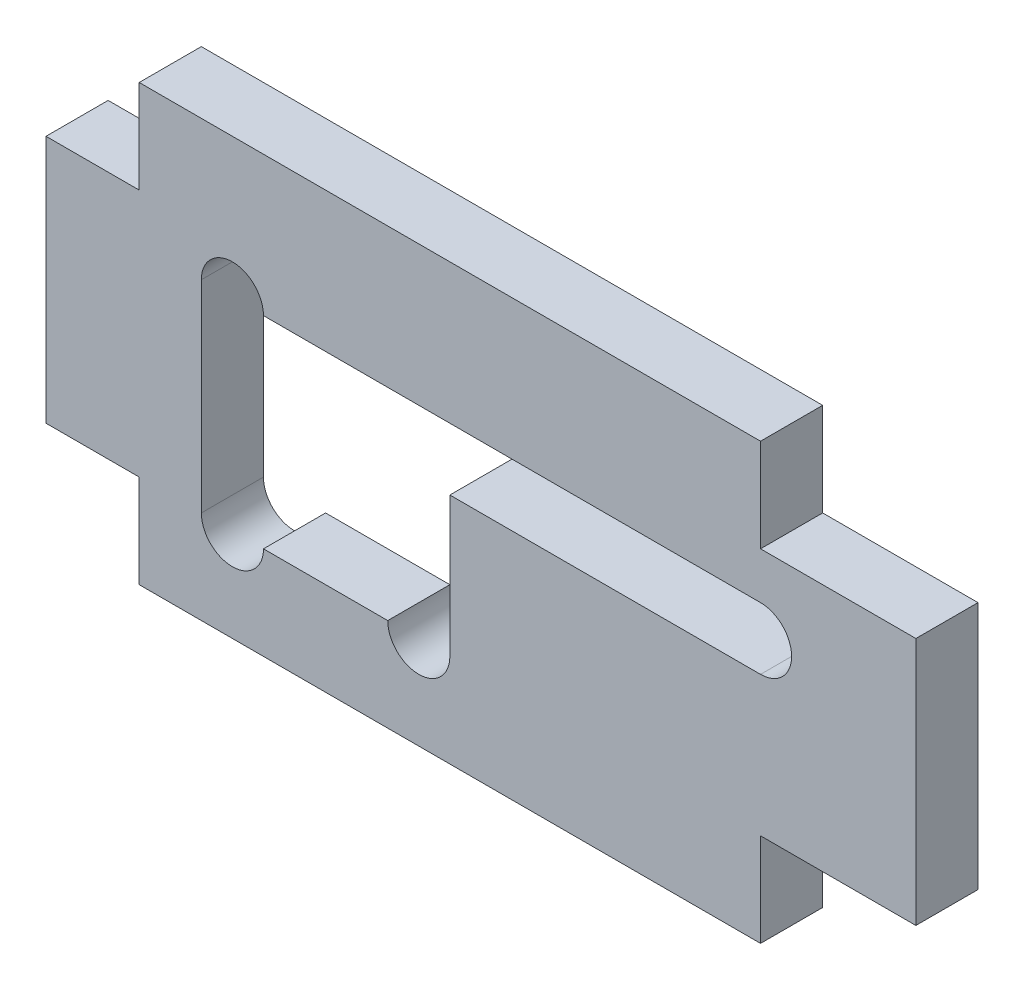
SolidWorks part; units mm, degrees
ref_plane "Front Plane" through (0, 0, 0) normal (0, 0, 1) x (1, 0, 0)
ref_plane "Top Plane" through (0, 0, 0) normal (0, 1, 0) x (1, 0, 0)
ref_plane "Right Plane" through (0, 0, 0) normal (1, 0, 0) x (0, 0, -1)
sketch "Sketch2" plane through (0, 0, 0) normal (0, 0, 1) x (1, 0, 0)
  line L0 (-100.4852, 17.2209) -> (-80.4852, 17.2209)
  line L1 (-80.4852, 17.2209) -> (-80.4852, 14.2209)
  line L2 (-80.4852, 14.2209) -> (-70.4852, 14.2209)
  line L3 (-70.4852, 14.2209) -> (-70.4852, 6.2209)
  line L4 (-70.4852, 6.2209) -> (-80.4852, 6.2209)
  line L5 (-80.4852, 6.2209) -> (-80.4852, 3.2209)
  line L6 (-80.4852, 3.2209) -> (-100.4852, 3.2209)
  line L7 (-100.4852, 3.2209) -> (-100.4852, 6.2209)
  line L8 (-100.4852, 6.2209) -> (-103.4852, 6.2209)
  line L9 (-103.4852, 6.2209) -> (-103.4852, 14.2209)
  line L10 (-103.4852, 14.2209) -> (-100.4852, 14.2209)
  line L11 (-100.4852, 14.2209) -> (-100.4852, 17.2209)
  line L13 (-90.4852, 10.7209) -> (-80.4852, 10.7209)
  line L14 (-98.4852, 12.7209) -> (-98.4852, 6.2209)
  line L16 (-90.4852, 6.2209) -> (-90.4852, 10.7209)
  line L17 (-96.4852, 12.7209) -> (-80.4852, 12.7209)
  line L18 (-96.4852, 6.2209) -> (-92.4852, 6.2209)
  arc A0 (-80.4852, 10.7209) -> (-80.4852, 12.7209) centre (-80.4852, 11.7209) ccw
  arc A1 (-96.4852, 12.7209) -> (-98.4852, 12.7209) centre (-97.4852, 12.7209) ccw
  arc A2 (-98.4852, 6.2209) -> (-96.4852, 6.2209) centre (-97.4852, 6.2209) ccw
  arc A3 (-92.4852, 6.2209) -> (-90.4852, 6.2209) centre (-91.4852, 6.2209) ccw
extrude "Boss-Extrude1" add sketch "Sketch2" along normal blind 2
sketch "Sketch3" plane through (0, 0, 2) normal (0, 0, 1) x (1, 0, 0)
  line L0 (-70.4852, 14.2209) -> (-75.4852, 14.2209)
  line L1 (-70.4852, 14.2209) -> (-80.4852, 14.2209) construction
  line L2 (-75.4852, 14.2209) -> (-75.4852, 6.2209)
  line L3 (-80.4852, 6.2209) -> (-70.4852, 6.2209) construction
  line L4 (-75.4852, 6.2209) -> (-70.4852, 6.2209)
  line L5 (-70.4852, 6.2209) -> (-70.4852, 14.2209)
extrude "Cut-Extrude1" cut sketch "Sketch3" against normal blind 2
